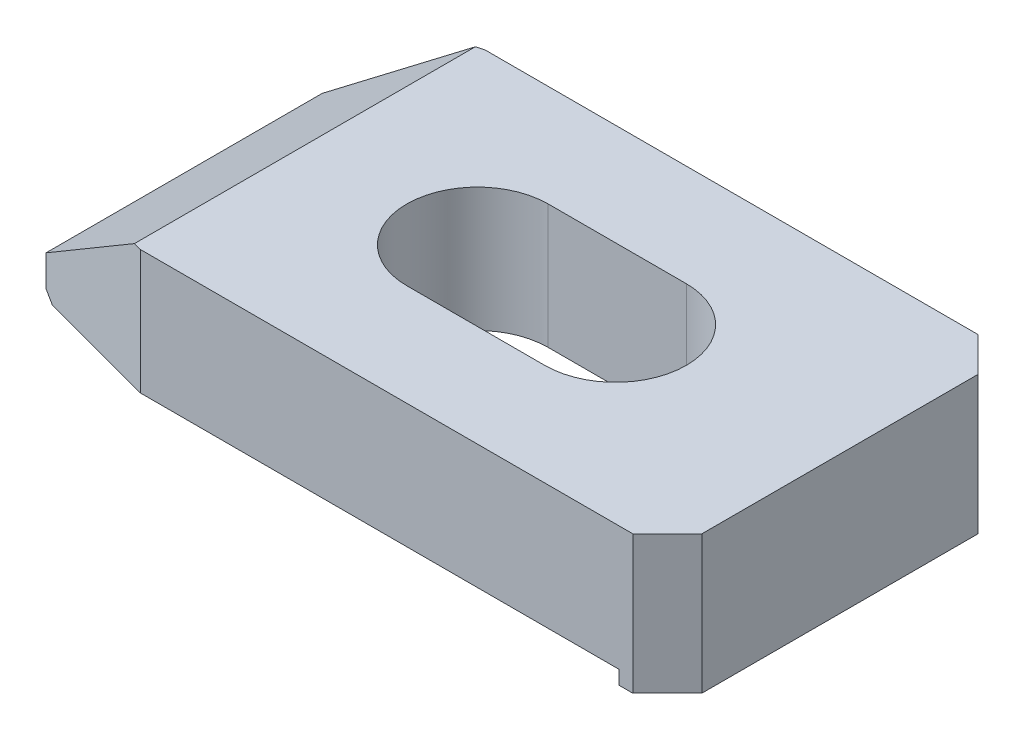
SolidWorks part; units mm, degrees
material "1.4301 (X5CrNi18-10) (KO33)"
ref_plane "Első Sík" through (0, 0, 0) normal (0, 0, 1) x (1, 0, 0)
ref_plane "Felső Sík" through (0, 0, 0) normal (0, 1, 0) x (1, 0, 0)
ref_plane "Jobb Sík" through (0, 0, 0) normal (1, 0, 0) x (0, 0, -1)
sketch "Sketch1" plane through (0, 0, 0) normal (0, 1, 0) x (1, 0, 0)
  line L0 (0, 0) -> (19, 0) construction
  line L1 (0, 5) -> (19, 5)
  line L2 (0, 5) -> (0, -5)
  line L3 (0, -5) -> (19, -5)
  line L4 (19, 5) -> (19, -5)
  line L5 (8.5, 0) -> (12.5, 0) construction
  line L6 (8.5, 2.05) -> (12.5, 2.05)
  line L7 (8.5, -2.05) -> (12.5, -2.05)
  arc A0 (8.5, 2.05) -> (8.5, -2.05) centre (8.5, 0) ccw
  arc A1 (12.5, -2.05) -> (12.5, 2.05) centre (12.5, 0) ccw
  point P9 (10.5, 0)
  dimension "D4" = 4
  dimension "D1" = 10
  dimension "D2" = 19
  dimension "D3" = 8.5
  dimension "D5" = 4.1
extrude "Boss-Extrude1" add sketch "Sketch1" along normal mid plane 4
sketch "Sketch2" plane through (0, -2, 0) normal (0, 1, 0) x (1, 0, 0)
  line L0 (0, -5) -> (19, -5) construction
  line L1 (0, 5) -> (17.6, 5)
  line L2 (0, 5) -> (0, -5)
  line L3 (0, -5) -> (17.6, -5)
  line L4 (17.6, 5) -> (17.6, -5)
  line L5 (19, -5) -> (19, 5) construction
  dimension "D1" = 1.4
sketch "Sketch4" plane through (0, 0, 0) normal (0, 0, 1) x (1, 0, 0)
  line L0 (0, 2) -> (19, 2) construction
  line L1 (19, 2) -> (19, -2) construction
  line L2 (0, -2) -> (19, -2) construction
  circle A0 centre (17, 0) radius 0.75
  dimension "D2" = 1.5
  dimension "D1" = 2
  dimension "D3" = 2
  dimension "D4" = 2
extrude "Cut-Extrude3" [suppressed] cut sketch "Sketch4" against normal mid plane 10 contours A0
chamfer "Chamfer2" distance 1 angle 45 2 edges at (19, 0, -5) (19, 0, 5)
extrude "Cut-Extrude4" cut sketch "Sketch2" along normal blind 0.4
sketch "Sketch5" plane through (0, 2, 0) normal (0, 1, 0) x (1, 0, 0)
  line L0 (0, 0) -> (6.45, 0) construction
  line L1 (0, 5) -> (0, -5) construction
  line L2 (0, 4) -> (3.7321, 5)
  line L3 (18, 5) -> (0, 5) construction
  line L4 (3.7321, 5) -> (0, 5)
  line L5 (0, 5) -> (0, 4)
  line L6 (0, -4) -> (0, -5)
  line L7 (0, -5) -> (3.7321, -5)
  line L8 (0, -5) -> (18, -5) construction
  line L9 (3.7321, -5) -> (0, -4)
  arc A0 (8.5, 2.05) -> (8.5, -2.05) centre (8.5, 0) ccw construction
  dimension "D1" = 8
  dimension "D2" = 15
extrude "Cut-Extrude5" cut sketch "Sketch5" against normal through all
chamfer "Chamfer4" distance 3.5 angle 35 1 edges at (0, 2, 0)
chamfer "Chamfer5" distance 0.25 angle 45 1 edges at (0, -1.6, 0)
